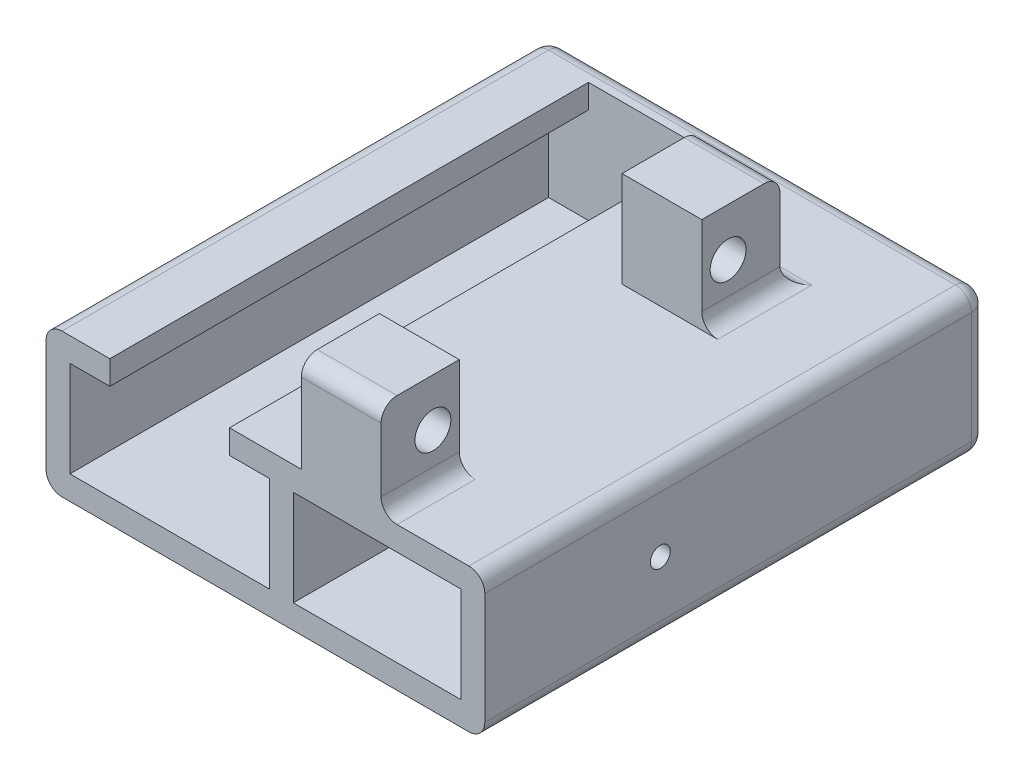
SolidWorks part; units mm, degrees
ref_plane "Front Plane" through (0, 0, 0) normal (0, 0, 1) x (1, 0, 0)
ref_plane "Top Plane" through (0, 0, 0) normal (0, 1, 0) x (1, 0, 0)
ref_plane "Right Plane" through (0, 0, 0) normal (1, 0, 0) x (0, 0, -1)
sketch "Sketch1" plane through (0, 0, 0) normal (0, 0, 1) x (1, 0, 0)
  line L0 (17.5093, 21.5886) -> (-9.4907, 21.5886)
  line L3 (-5.4907, 21.5886) -> (13.5093, 21.5886) construction
  line L4 (-11.4907, 21.5886) -> (-7.4907, 21.5886) construction
  line L5 (-9.4907, 18.5886) -> (-9.4907, 6.5886)
  line L6 (-9.4907, 6.5886) -> (-34.4907, 6.5886)
  line L7 (-34.4907, 6.5886) -> (-34.4907, 18.5886)
  line L8 (-34.4907, 21.5886) -> (-37.4907, 21.5886)
  line L9 (-37.4907, 21.5886) -> (-37.4907, 3.5886)
  line L10 (-37.4907, 3.5886) -> (17.5093, 3.5886)
  line L11 (17.5093, 3.5886) -> (17.5093, 21.5886)
  line L12 (-7.4907, 26.1744) -> (-7.4907, 22.5886) construction
  line L14 (14.5093, 18.5886) -> (-6.4907, 18.5886)
  line L15 (14.5093, 18.5886) -> (14.5093, 6.5886)
  line L16 (14.5093, 6.5886) -> (-6.4907, 6.5886)
  line L17 (-6.4907, 18.5886) -> (-6.4907, 6.5886)
  line L18 (-9.4907, 21.5886) -> (-14.4907, 21.5886)
  line L20 (-9.4907, 18.5886) -> (-14.4907, 18.5886)
  line L21 (-14.4907, 21.5886) -> (-14.4907, 18.5886)
  line L22 (-34.4907, 21.5886) -> (-29.4907, 21.5886)
  line L24 (-34.4907, 18.5886) -> (-29.4907, 18.5886)
  line L25 (-29.4907, 21.5886) -> (-29.4907, 18.5886)
  dimension "D1" = 2
  dimension "D2" = 25
  dimension "D3" = 3
  dimension "D4" = 55
  dimension "D5" = 3
  dimension "D6" = 15
  dimension "D7" = 3
  dimension "D8" = 3
  dimension "D9" = 3
  dimension "D10" = 3
  dimension "D11" = 3
  dimension "D12" = 3
  dimension "D13" = 5
  dimension "D14" = 5
extrude "Boss-Extrude1" add sketch "Sketch1" against normal blind 60
sketch "Sketch2" plane through (-5.4907, 0, 0) normal (1, 0, 0) x (0, 0, -1)
  line L0 (39, 33.5886) -> (44.25, 33.5886) construction
  line L1 (50, 21.5886) -> (40.2, 21.5886)
  line L2 (50, 21.5886) -> (50, 31.5886)
  line L3 (48, 33.5886) -> (40.2, 33.5886)
  line L4 (40.2, 21.5886) -> (40.2, 33.5886)
  line L5 (40, 32.5886) -> (40, 22.5886) construction
  line L6 (60, 21.5886) -> (0, 21.5886) construction
  line L7 (9.8, 21.5886) -> (0, 21.5886)
  line L8 (9.8, 21.5886) -> (9.8, 33.5886)
  line L9 (9.8, 33.5886) -> (2, 33.5886)
  line L10 (0, 21.5886) -> (0, 31.5886)
  line L11 (10, 22.5886) -> (10, 32.5886) construction
  line L12 (5.75, 33.5886) -> (11, 33.5886) construction
  line L13 (0, 3.5886) -> (0, 21.5886) construction
  circle A0 centre (43.5, 27.5886) radius 2.25
  circle A1 centre (6.5, 27.5886) radius 2.25
  arc A2 (50, 31.5886) -> (48, 33.5886) centre (48, 31.5886) ccw
  arc A3 (2, 33.5886) -> (0, 31.5886) centre (2, 31.5886) ccw
  dimension "D2" = 4.5
  dimension "D4" = 4.5
  dimension "D5" = 2
  dimension "D1" = 0.2
  dimension "D3" = 0.2
  dimension "D6" = 9.8
extrude "Boss-Extrude2" add sketch "Sketch2" along normal blind 10
sketch "Sketch3" plane through (0, 0, -60) normal (0, 0, -1) x (-1, 0, 0)
  line L1 (-17.5093, 21.5886) -> (37.4907, 21.5886)
  line L2 (-17.5093, 21.5886) -> (-17.5093, 3.5886)
  line L3 (-17.5093, 3.5886) -> (37.4907, 3.5886)
  line L4 (37.4907, 21.5886) -> (37.4907, 3.5886)
extrude "Boss-Extrude3" add sketch "Sketch3" along normal blind 3
fillet "Fillet1" radius 2 11 edges at (17.5093, 21.5886, -31.5) (17.5093, 3.5886, -31.5) (-37.4907, 3.5886, -31.5) (-37.4907, 21.5886, -31.5) (-9.9907, 21.5886, -63) (-37.4907, 12.5886, -63) (-9.9907, 3.5886, -63) (17.5093, 12.5886, -63) (4.5093, 21.5886, -4.9) (-0.4907, 21.5886, -50) (4.5093, 21.5886, -45.1)
sketch "Sketch4" plane through (17.5093, 0, 0) normal (1, 0, 0) x (0, 0, -1)
  line L0 (0, 12.5886) -> (61, 12.5886) construction
  line L1 (0, 5.5886) -> (0, 19.5886) construction
  line L2 (61, 5.5886) -> (61, 19.5886) construction
  circle A0 centre (22, 12.5886) radius 1.25
  dimension "D1" = 2.5
  dimension "D2" = 22
extrude "Cut-Extrude1" cut sketch "Sketch4" against normal blind 30
